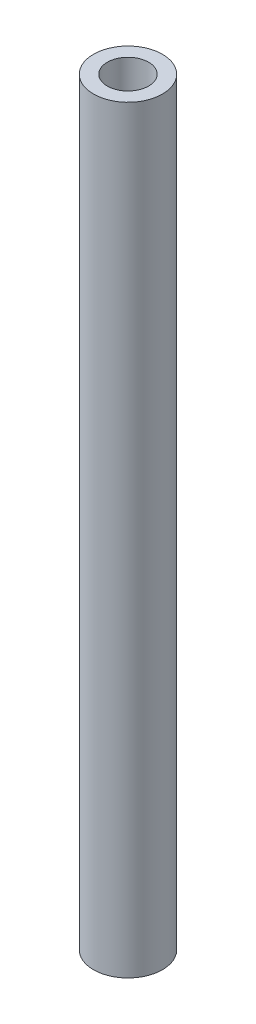
SolidWorks part; units mm, degrees
material "1060 合金"
ref_plane "前视基准面" through (0, 0, 0) normal (0, 0, 1) x (1, 0, 0)
ref_plane "上视基准面" through (0, 0, 0) normal (0, 1, 0) x (1, 0, 0)
ref_plane "右视基准面" through (0, 0, 0) normal (1, 0, 0) x (0, 0, -1)
other "Configuration Table"
sketch "草图1" plane through (0, 0, 0) normal (0, 1, 0) x (1, 0, 0)
  circle A0 centre (0, 0) radius 2.5
  circle A1 centre (0, 0) radius 1.5
  dimension "D1" = 3
  dimension "5" = 5
extrude "凸台-拉伸1" add sketch "草图1" along normal blind 55
